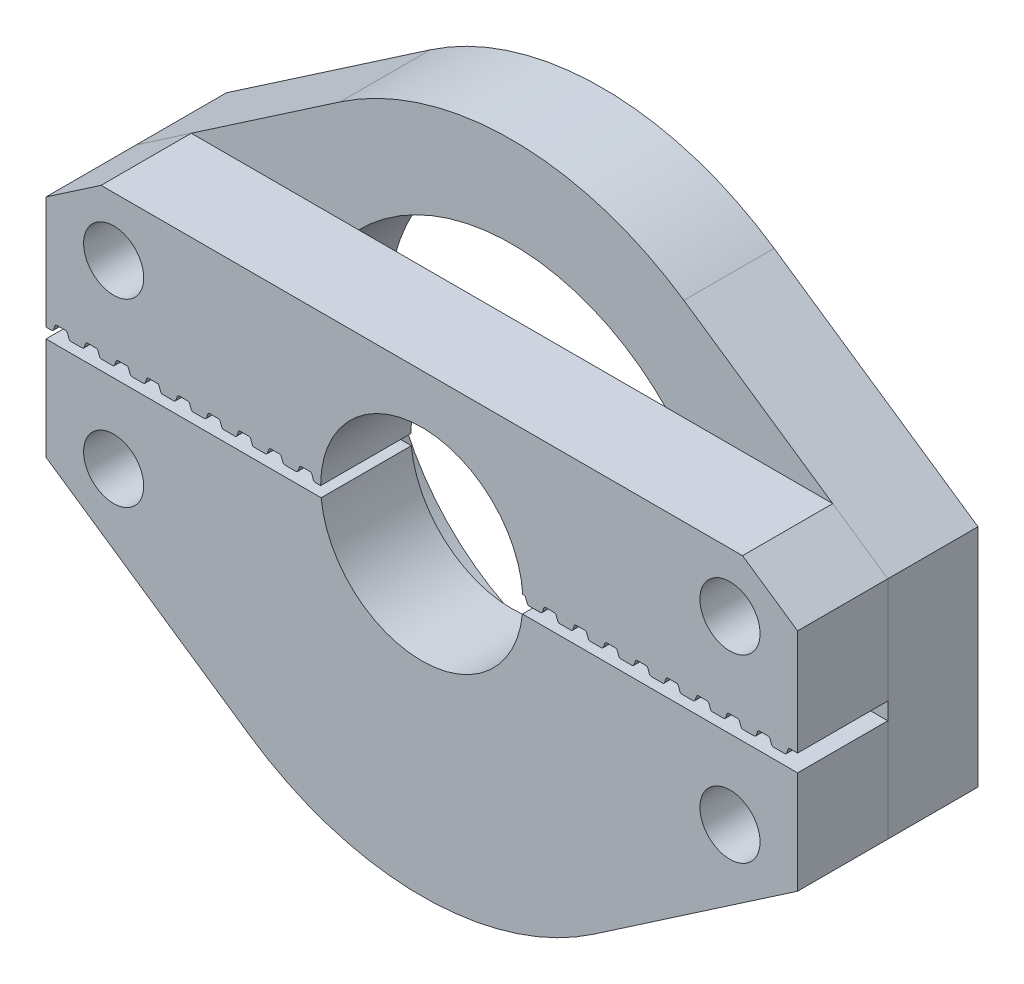
SolidWorks part; units mm, degrees
ref_plane "Front Plane" through (0, 0, 0) normal (0, 0, 1) x (1, 0, 0)
ref_plane "Top Plane" through (0, 0, 0) normal (0, 1, 0) x (1, 0, 0)
ref_plane "Right Plane" through (0, 0, 0) normal (1, 0, 0) x (0, 0, -1)
sketch "Sketch1" plane through (0, 0, 0) normal (0, 0, 1) x (1, 0, 0)
  line L0 (-45.5994, 0) -> (48.5496, 0) construction
  line L1 (-25, 7.5) -> (25, 7.5) construction
  line L2 (0, 0) -> (0, 53.2444) construction
  line L3 (-25, -7.5) -> (25, -7.5) construction
  line L4 (-25, 7.5) -> (-25, -7.5)
  line L5 (-25, -7.5) -> (-11.4362, -16.757)
  line L6 (-25, 7.5) -> (-11.4362, 16.757)
  line L7 (25, 7.5) -> (25, -7.5)
  line L8 (25, -7.5) -> (11.4362, -16.757)
  line L9 (25, 7.5) -> (11.4362, 16.757)
  circle A0 centre (0, 0) radius 14.2875
  arc A1 (-11.4362, -16.757) -> (11.4362, -16.757) centre (0, 0) ccw
  circle A2 centre (0, 0) radius 20.2875 construction
  arc A3 (11.4362, 16.757) -> (-11.4362, 16.757) centre (0, 0) ccw
  dimension "D1" = 28.575
  dimension "D3" = 50
  dimension "D4" = 15
  dimension "D2" = 6
extrude "Extrude1" add sketch "Sketch1" along normal blind 6
sketch "Sketch2" plane through (0, 0, 6) normal (0, 0, 1) x (1, 0, 0)
  line L0 (-25, 0) -> (25, 0) construction
  line L1 (-25, 7.5) -> (-25, -7.5) construction
  line L2 (25, -7.5) -> (25, 7.5) construction
  line L3 (-25, -0.68) -> (25, -0.68)
  line L4 (25, 7.5) -> (11.4362, 16.757) construction
  line L5 (-11.4362, 16.757) -> (-25, 7.5) construction
  line L6 (25, 7.5) -> (21.3369, 10)
  line L7 (-25, -0.68) -> (-25, -7.5)
  line L8 (0, 0) -> (0, 10) construction
  line L9 (-25, 0.46) -> (25, 0.46) construction
  line L10 (-25, 0) -> (-24.6225, 0)
  line L11 (-24.5003, 0.0855) -> (-24.3951, 0.3745)
  line L12 (-24.273, 0.46) -> (-23.695, 0.46)
  line L13 (-23.5729, 0.3745) -> (-23.4677, 0.0855)
  line L14 (-23.3455, 0) -> (-22.968, 0)
  line L15 (-23.984, 0.46) -> (-23.984, -0.2889) construction
  line L16 (-25, 0) -> (-25, 7.5)
  line L17 (-21.3369, 10) -> (-25, 7.5)
  line L18 (25, 7.5) -> (25, 0.46)
  line L19 (25, -0.68) -> (25, -7.5)
  line L20 (-25, -7.5) -> (-11.4362, -16.757) construction
  line L21 (11.4362, -16.757) -> (25, -7.5) construction
  line L22 (-25, -7.5) -> (-11.4362, -16.757)
  line L23 (11.4362, -16.757) -> (25, -7.5)
  line L24 (-21.3369, 10) -> (21.3369, 10)
  line L25 (0, 20.2875) -> (0, 25.9444) construction
  line L151 (-22.968, 0) -> (-22.5905, 0)
  line L152 (-22.4683, 0.0855) -> (-22.3631, 0.3745)
  line L153 (-22.241, 0.46) -> (-21.663, 0.46)
  line L154 (-21.5409, 0.3745) -> (-21.4357, 0.0855)
  line L155 (-21.3135, 0) -> (-20.936, 0)
  line L156 (-20.936, 0) -> (-20.5585, 0)
  line L157 (-20.4363, 0.0855) -> (-20.3311, 0.3745)
  line L158 (-20.209, 0.46) -> (-19.631, 0.46)
  line L159 (-19.5089, 0.3745) -> (-19.4037, 0.0855)
  line L160 (-19.2815, 0) -> (-18.904, 0)
  line L161 (-18.904, 0) -> (-18.5265, 0)
  line L162 (-18.4043, 0.0855) -> (-18.2991, 0.3745)
  line L163 (-18.177, 0.46) -> (-17.599, 0.46)
  line L164 (-17.4769, 0.3745) -> (-17.3717, 0.0855)
  line L165 (-17.2495, 0) -> (-16.872, 0)
  line L166 (-16.872, 0) -> (-16.4945, 0)
  line L167 (-16.3723, 0.0855) -> (-16.2671, 0.3745)
  line L168 (-16.145, 0.46) -> (-15.567, 0.46)
  line L169 (-15.4449, 0.3745) -> (-15.3397, 0.0855)
  line L170 (-15.2175, 0) -> (-14.84, 0)
  line L171 (-14.84, 0) -> (-14.4625, 0)
  line L172 (-14.3403, 0.0855) -> (-14.2351, 0.3745)
  line L173 (-14.113, 0.46) -> (-13.535, 0.46)
  line L174 (-13.4129, 0.3745) -> (-13.3077, 0.0855)
  line L175 (-13.1855, 0) -> (-12.808, 0)
  line L176 (-12.808, 0) -> (-12.4305, 0)
  line L177 (-12.3083, 0.0855) -> (-12.2031, 0.3745)
  line L178 (-12.081, 0.46) -> (-11.503, 0.46)
  line L179 (-11.3809, 0.3745) -> (-11.2757, 0.0855)
  line L180 (-11.1535, 0) -> (-10.776, 0)
  line L181 (-10.776, 0) -> (-10.3985, 0)
  line L182 (-10.2763, 0.0855) -> (-10.1711, 0.3745)
  line L183 (-10.049, 0.46) -> (-9.471, 0.46)
  line L184 (-9.3489, 0.3745) -> (-9.2437, 0.0855)
  line L185 (-9.1215, 0) -> (-8.744, 0)
  line L186 (-8.744, 0) -> (-8.3665, 0)
  line L187 (-8.2443, 0.0855) -> (-8.1391, 0.3745)
  line L188 (-8.017, 0.46) -> (-7.439, 0.46)
  line L189 (-7.3169, 0.3745) -> (-7.2117, 0.0855)
  line L190 (-7.0895, 0) -> (-6.712, 0)
  line L191 (-6.712, 0) -> (-6.3345, 0)
  line L192 (-6.2123, 0.0855) -> (-6.1071, 0.3745)
  line L193 (-5.985, 0.46) -> (-5.407, 0.46)
  line L194 (-5.2849, 0.3745) -> (-5.1797, 0.0855)
  line L195 (-5.0575, 0) -> (-4.68, 0)
  line L196 (-4.68, 0) -> (-4.3025, 0)
  line L197 (-4.1803, 0.0855) -> (-4.0751, 0.3745)
  line L198 (-3.953, 0.46) -> (-3.375, 0.46)
  line L199 (-3.2529, 0.3745) -> (-3.1477, 0.0855)
  line L200 (-3.0255, 0) -> (-2.648, 0)
  line L201 (-2.648, 0) -> (-2.2705, 0)
  line L202 (-2.1483, 0.0855) -> (-2.0431, 0.3745)
  line L203 (-1.921, 0.46) -> (-1.343, 0.46)
  line L204 (-1.2209, 0.3745) -> (-1.1157, 0.0855)
  line L205 (-0.9935, 0) -> (-0.616, 0)
  line L206 (-0.616, 0) -> (-0.2385, 0)
  line L207 (-0.1163, 0.0855) -> (-0.0111, 0.3745)
  line L208 (0.111, 0.46) -> (0.689, 0.46)
  line L209 (0.8111, 0.3745) -> (0.9163, 0.0855)
  line L210 (1.0385, 0) -> (1.416, 0)
  line L211 (1.416, 0) -> (1.7935, 0)
  line L212 (1.9157, 0.0855) -> (2.0209, 0.3745)
  line L213 (2.143, 0.46) -> (2.721, 0.46)
  line L214 (2.8431, 0.3745) -> (2.9483, 0.0855)
  line L215 (3.0705, 0) -> (3.448, 0)
  line L216 (3.448, 0) -> (3.8255, 0)
  line L217 (3.9477, 0.0855) -> (4.0529, 0.3745)
  line L218 (4.175, 0.46) -> (4.753, 0.46)
  line L219 (4.8751, 0.3745) -> (4.9803, 0.0855)
  line L220 (5.1025, 0) -> (5.48, 0)
  line L221 (5.48, 0) -> (5.8575, 0)
  line L222 (5.9797, 0.0855) -> (6.0849, 0.3745)
  line L223 (6.207, 0.46) -> (6.785, 0.46)
  line L224 (6.9071, 0.3745) -> (7.0123, 0.0855)
  line L225 (7.1345, 0) -> (7.512, 0)
  line L226 (7.512, 0) -> (7.8895, 0)
  line L227 (8.0117, 0.0855) -> (8.1169, 0.3745)
  line L228 (8.239, 0.46) -> (8.817, 0.46)
  line L229 (8.9391, 0.3745) -> (9.0443, 0.0855)
  line L230 (9.1665, 0) -> (9.544, 0)
  line L231 (9.544, 0) -> (9.9215, 0)
  line L232 (10.0437, 0.0855) -> (10.1489, 0.3745)
  line L233 (10.271, 0.46) -> (10.849, 0.46)
  line L234 (10.9711, 0.3745) -> (11.0763, 0.0855)
  line L235 (11.1985, 0) -> (11.576, 0)
  line L236 (11.576, 0) -> (11.9535, 0)
  line L237 (12.0757, 0.0855) -> (12.1809, 0.3745)
  line L238 (12.303, 0.46) -> (12.881, 0.46)
  line L239 (13.0031, 0.3745) -> (13.1083, 0.0855)
  line L240 (13.2305, 0) -> (13.608, 0)
  line L241 (13.608, 0) -> (13.9855, 0)
  line L242 (14.1077, 0.0855) -> (14.2129, 0.3745)
  line L243 (14.335, 0.46) -> (14.913, 0.46)
  line L244 (15.0351, 0.3745) -> (15.1403, 0.0855)
  line L245 (15.2625, 0) -> (15.64, 0)
  line L246 (15.64, 0) -> (16.0175, 0)
  line L247 (16.1397, 0.0855) -> (16.2449, 0.3745)
  line L248 (16.367, 0.46) -> (16.945, 0.46)
  line L249 (17.0671, 0.3745) -> (17.1723, 0.0855)
  line L250 (17.2945, 0) -> (17.672, 0)
  line L251 (17.672, 0) -> (18.0495, 0)
  line L252 (18.1717, 0.0855) -> (18.2769, 0.3745)
  line L253 (18.399, 0.46) -> (18.977, 0.46)
  line L254 (19.0991, 0.3745) -> (19.2043, 0.0855)
  line L255 (19.3265, 0) -> (19.704, 0)
  line L256 (19.704, 0) -> (20.0815, 0)
  line L257 (20.2037, 0.0855) -> (20.3089, 0.3745)
  line L258 (20.431, 0.46) -> (21.009, 0.46)
  line L259 (21.1311, 0.3745) -> (21.2363, 0.0855)
  line L260 (21.3585, 0) -> (21.736, 0)
  line L261 (21.736, 0) -> (22.1135, 0)
  line L262 (22.2357, 0.0855) -> (22.3409, 0.3745)
  line L263 (22.463, 0.46) -> (23.041, 0.46)
  line L264 (23.1631, 0.3745) -> (23.2683, 0.0855)
  line L265 (23.3905, 0) -> (23.768, 0)
  line L266 (23.768, 0) -> (24.1455, 0)
  line L267 (24.2677, 0.0855) -> (24.3729, 0.3745)
  line L268 (24.495, 0.46) -> (25, 0.46)
  line L296 (35.3551, 0.3745) -> (35.4603, 0.0855) [skipped]
  line L297 (35.5825, 0) -> (35.96, 0) [skipped]
  line L298 (25.1951, 0.3745) -> (25.3003, 0.0855) [skipped]
  line L299 (25.4225, 0) -> (25.8, 0) [skipped]
  line L300 (25.8, 0) -> (26.1775, 0) [skipped]
  line L301 (26.2997, 0.0855) -> (26.4049, 0.3745) [skipped]
  line L302 (26.527, 0.46) -> (27.105, 0.46) [skipped]
  line L303 (27.2271, 0.3745) -> (27.3323, 0.0855) [skipped]
  line L304 (27.4545, 0) -> (27.832, 0) [skipped]
  line L305 (27.832, 0) -> (28.2095, 0) [skipped]
  line L306 (28.3317, 0.0855) -> (28.4369, 0.3745) [skipped]
  line L307 (28.559, 0.46) -> (29.137, 0.46) [skipped]
  line L308 (29.2591, 0.3745) -> (29.3643, 0.0855) [skipped]
  line L309 (29.4865, 0) -> (29.864, 0) [skipped]
  line L310 (29.864, 0) -> (30.2415, 0) [skipped]
  line L311 (30.3637, 0.0855) -> (30.4689, 0.3745) [skipped]
  line L312 (30.591, 0.46) -> (31.169, 0.46) [skipped]
  line L313 (31.2911, 0.3745) -> (31.3963, 0.0855) [skipped]
  line L314 (31.5185, 0) -> (31.896, 0) [skipped]
  line L315 (31.896, 0) -> (32.2735, 0) [skipped]
  line L316 (32.3957, 0.0855) -> (32.5009, 0.3745) [skipped]
  line L317 (32.623, 0.46) -> (33.201, 0.46) [skipped]
  line L318 (33.3231, 0.3745) -> (33.4283, 0.0855) [skipped]
  line L319 (33.5505, 0) -> (33.928, 0) [skipped]
  line L320 (33.928, 0) -> (34.3055, 0) [skipped]
  line L321 (34.4277, 0.0855) -> (34.5329, 0.3745) [skipped]
  line L322 (34.655, 0.46) -> (26.527, 0.46) [skipped]
  arc A0 (-24.5003, 0.0855) -> (-24.6225, 0) centre (-24.6225, 0.13) cw
  arc A1 (-24.273, 0.46) -> (-24.3951, 0.3745) centre (-24.273, 0.33) ccw
  arc A2 (-23.5729, 0.3745) -> (-23.695, 0.46) centre (-23.695, 0.33) ccw
  arc A3 (-23.3455, 0) -> (-23.4677, 0.0855) centre (-23.3455, 0.13) cw
  arc A6 (-11.4362, -16.757) -> (11.4362, -16.757) centre (0, 0) ccw construction
  arc A7 (-11.4362, -16.757) -> (11.4362, -16.757) centre (0, 0) ccw
  arc A112 (-22.4683, 0.0855) -> (-22.5905, 0) centre (-22.5905, 0.13) cw
  arc A113 (-22.241, 0.46) -> (-22.3631, 0.3745) centre (-22.241, 0.33) ccw
  arc A114 (-21.5409, 0.3745) -> (-21.663, 0.46) centre (-21.663, 0.33) ccw
  arc A115 (-21.3135, 0) -> (-21.4357, 0.0855) centre (-21.3135, 0.13) cw
  arc A116 (-20.4363, 0.0855) -> (-20.5585, 0) centre (-20.5585, 0.13) cw
  arc A117 (-20.209, 0.46) -> (-20.3311, 0.3745) centre (-20.209, 0.33) ccw
  arc A118 (-19.5089, 0.3745) -> (-19.631, 0.46) centre (-19.631, 0.33) ccw
  arc A119 (-19.2815, 0) -> (-19.4037, 0.0855) centre (-19.2815, 0.13) cw
  arc A120 (-18.4043, 0.0855) -> (-18.5265, 0) centre (-18.5265, 0.13) cw
  arc A121 (-18.177, 0.46) -> (-18.2991, 0.3745) centre (-18.177, 0.33) ccw
  arc A122 (-17.4769, 0.3745) -> (-17.599, 0.46) centre (-17.599, 0.33) ccw
  arc A123 (-17.2495, 0) -> (-17.3717, 0.0855) centre (-17.2495, 0.13) cw
  arc A124 (-16.3723, 0.0855) -> (-16.4945, 0) centre (-16.4945, 0.13) cw
  arc A125 (-16.145, 0.46) -> (-16.2671, 0.3745) centre (-16.145, 0.33) ccw
  arc A126 (-15.4449, 0.3745) -> (-15.567, 0.46) centre (-15.567, 0.33) ccw
  arc A127 (-15.2175, 0) -> (-15.3397, 0.0855) centre (-15.2175, 0.13) cw
  arc A128 (-14.3403, 0.0855) -> (-14.4625, 0) centre (-14.4625, 0.13) cw
  arc A129 (-14.113, 0.46) -> (-14.2351, 0.3745) centre (-14.113, 0.33) ccw
  arc A130 (-13.4129, 0.3745) -> (-13.535, 0.46) centre (-13.535, 0.33) ccw
  arc A131 (-13.1855, 0) -> (-13.3077, 0.0855) centre (-13.1855, 0.13) cw
  arc A132 (-12.3083, 0.0855) -> (-12.4305, 0) centre (-12.4305, 0.13) cw
  arc A133 (-12.081, 0.46) -> (-12.2031, 0.3745) centre (-12.081, 0.33) ccw
  arc A134 (-11.3809, 0.3745) -> (-11.503, 0.46) centre (-11.503, 0.33) ccw
  arc A135 (-11.1535, 0) -> (-11.2757, 0.0855) centre (-11.1535, 0.13) cw
  arc A136 (-10.2763, 0.0855) -> (-10.3985, 0) centre (-10.3985, 0.13) cw
  arc A137 (-10.049, 0.46) -> (-10.1711, 0.3745) centre (-10.049, 0.33) ccw
  arc A138 (-9.3489, 0.3745) -> (-9.471, 0.46) centre (-9.471, 0.33) ccw
  arc A139 (-9.1215, 0) -> (-9.2437, 0.0855) centre (-9.1215, 0.13) cw
  arc A140 (-8.2443, 0.0855) -> (-8.3665, 0) centre (-8.3665, 0.13) cw
  arc A141 (-8.017, 0.46) -> (-8.1391, 0.3745) centre (-8.017, 0.33) ccw
  arc A142 (-7.3169, 0.3745) -> (-7.439, 0.46) centre (-7.439, 0.33) ccw
  arc A143 (-7.0895, 0) -> (-7.2117, 0.0855) centre (-7.0895, 0.13) cw
  arc A144 (-6.2123, 0.0855) -> (-6.3345, 0) centre (-6.3345, 0.13) cw
  arc A145 (-5.985, 0.46) -> (-6.1071, 0.3745) centre (-5.985, 0.33) ccw
  arc A146 (-5.2849, 0.3745) -> (-5.407, 0.46) centre (-5.407, 0.33) ccw
  arc A147 (-5.0575, 0) -> (-5.1797, 0.0855) centre (-5.0575, 0.13) cw
  arc A148 (-4.1803, 0.0855) -> (-4.3025, 0) centre (-4.3025, 0.13) cw
  arc A149 (-3.953, 0.46) -> (-4.0751, 0.3745) centre (-3.953, 0.33) ccw
  arc A150 (-3.2529, 0.3745) -> (-3.375, 0.46) centre (-3.375, 0.33) ccw
  arc A151 (-3.0255, 0) -> (-3.1477, 0.0855) centre (-3.0255, 0.13) cw
  arc A152 (-2.1483, 0.0855) -> (-2.2705, 0) centre (-2.2705, 0.13) cw
  arc A153 (-1.921, 0.46) -> (-2.0431, 0.3745) centre (-1.921, 0.33) ccw
  arc A154 (-1.2209, 0.3745) -> (-1.343, 0.46) centre (-1.343, 0.33) ccw
  arc A155 (-0.9935, 0) -> (-1.1157, 0.0855) centre (-0.9935, 0.13) cw
  arc A156 (-0.1163, 0.0855) -> (-0.2385, 0) centre (-0.2385, 0.13) cw
  arc A157 (0.111, 0.46) -> (-0.0111, 0.3745) centre (0.111, 0.33) ccw
  arc A158 (0.8111, 0.3745) -> (0.689, 0.46) centre (0.689, 0.33) ccw
  arc A159 (1.0385, 0) -> (0.9163, 0.0855) centre (1.0385, 0.13) cw
  arc A160 (1.9157, 0.0855) -> (1.7935, 0) centre (1.7935, 0.13) cw
  arc A161 (2.143, 0.46) -> (2.0209, 0.3745) centre (2.143, 0.33) ccw
  arc A162 (2.8431, 0.3745) -> (2.721, 0.46) centre (2.721, 0.33) ccw
  arc A163 (3.0705, 0) -> (2.9483, 0.0855) centre (3.0705, 0.13) cw
  arc A164 (3.9477, 0.0855) -> (3.8255, 0) centre (3.8255, 0.13) cw
  arc A165 (4.175, 0.46) -> (4.0529, 0.3745) centre (4.175, 0.33) ccw
  arc A166 (4.8751, 0.3745) -> (4.753, 0.46) centre (4.753, 0.33) ccw
  arc A167 (5.1025, 0) -> (4.9803, 0.0855) centre (5.1025, 0.13) cw
  arc A168 (5.9797, 0.0855) -> (5.8575, 0) centre (5.8575, 0.13) cw
  arc A169 (6.207, 0.46) -> (6.0849, 0.3745) centre (6.207, 0.33) ccw
  arc A170 (6.9071, 0.3745) -> (6.785, 0.46) centre (6.785, 0.33) ccw
  arc A171 (7.1345, 0) -> (7.0123, 0.0855) centre (7.1345, 0.13) cw
  arc A172 (8.0117, 0.0855) -> (7.8895, 0) centre (7.8895, 0.13) cw
  arc A173 (8.239, 0.46) -> (8.1169, 0.3745) centre (8.239, 0.33) ccw
  arc A174 (8.9391, 0.3745) -> (8.817, 0.46) centre (8.817, 0.33) ccw
  arc A175 (9.1665, 0) -> (9.0443, 0.0855) centre (9.1665, 0.13) cw
  arc A176 (10.0437, 0.0855) -> (9.9215, 0) centre (9.9215, 0.13) cw
  arc A177 (10.271, 0.46) -> (10.1489, 0.3745) centre (10.271, 0.33) ccw
  arc A178 (10.9711, 0.3745) -> (10.849, 0.46) centre (10.849, 0.33) ccw
  arc A179 (11.1985, 0) -> (11.0763, 0.0855) centre (11.1985, 0.13) cw
  arc A180 (12.0757, 0.0855) -> (11.9535, 0) centre (11.9535, 0.13) cw
  arc A181 (12.303, 0.46) -> (12.1809, 0.3745) centre (12.303, 0.33) ccw
  arc A182 (13.0031, 0.3745) -> (12.881, 0.46) centre (12.881, 0.33) ccw
  arc A183 (13.2305, 0) -> (13.1083, 0.0855) centre (13.2305, 0.13) cw
  arc A184 (14.1077, 0.0855) -> (13.9855, 0) centre (13.9855, 0.13) cw
  arc A185 (14.335, 0.46) -> (14.2129, 0.3745) centre (14.335, 0.33) ccw
  arc A186 (15.0351, 0.3745) -> (14.913, 0.46) centre (14.913, 0.33) ccw
  arc A187 (15.2625, 0) -> (15.1403, 0.0855) centre (15.2625, 0.13) cw
  arc A188 (16.1397, 0.0855) -> (16.0175, 0) centre (16.0175, 0.13) cw
  arc A189 (16.367, 0.46) -> (16.2449, 0.3745) centre (16.367, 0.33) ccw
  arc A190 (17.0671, 0.3745) -> (16.945, 0.46) centre (16.945, 0.33) ccw
  arc A191 (17.2945, 0) -> (17.1723, 0.0855) centre (17.2945, 0.13) cw
  arc A192 (18.1717, 0.0855) -> (18.0495, 0) centre (18.0495, 0.13) cw
  arc A193 (18.399, 0.46) -> (18.2769, 0.3745) centre (18.399, 0.33) ccw
  arc A194 (19.0991, 0.3745) -> (18.977, 0.46) centre (18.977, 0.33) ccw
  arc A195 (19.3265, 0) -> (19.2043, 0.0855) centre (19.3265, 0.13) cw
  arc A196 (20.2037, 0.0855) -> (20.0815, 0) centre (20.0815, 0.13) cw
  arc A197 (20.431, 0.46) -> (20.3089, 0.3745) centre (20.431, 0.33) ccw
  arc A198 (21.1311, 0.3745) -> (21.009, 0.46) centre (21.009, 0.33) ccw
  arc A199 (21.3585, 0) -> (21.2363, 0.0855) centre (21.3585, 0.13) cw
  arc A200 (22.2357, 0.0855) -> (22.1135, 0) centre (22.1135, 0.13) cw
  arc A201 (22.463, 0.46) -> (22.3409, 0.3745) centre (22.463, 0.33) ccw
  arc A202 (23.1631, 0.3745) -> (23.041, 0.46) centre (23.041, 0.33) ccw
  arc A203 (23.3905, 0) -> (23.2683, 0.0855) centre (23.3905, 0.13) cw
  arc A204 (24.2677, 0.0855) -> (24.1455, 0) centre (24.1455, 0.13) cw
  arc A205 (24.495, 0.46) -> (24.3729, 0.3745) centre (24.495, 0.33) ccw
  arc A228 (35.3551, 0.3745) -> (35.233, 0.46) centre (35.233, 0.33) ccw [skipped]
  arc A229 (35.5825, 0) -> (35.4603, 0.0855) centre (35.5825, 0.13) cw [skipped]
  arc A230 (25.4225, 0) -> (25.3003, 0.0855) centre (25.4225, 0.13) cw [skipped]
  arc A231 (25.1951, 0.3745) -> (25.073, 0.46) centre (25.073, 0.33) ccw [skipped]
  arc A232 (26.2997, 0.0855) -> (26.1775, 0) centre (26.1775, 0.13) cw [skipped]
  arc A233 (26.527, 0.46) -> (26.4049, 0.3745) centre (26.527, 0.33) ccw [skipped]
  arc A234 (27.2271, 0.3745) -> (27.105, 0.46) centre (27.105, 0.33) ccw [skipped]
  arc A235 (27.4545, 0) -> (27.3323, 0.0855) centre (27.4545, 0.13) cw [skipped]
  arc A236 (28.3317, 0.0855) -> (28.2095, 0) centre (28.2095, 0.13) cw [skipped]
  arc A237 (28.559, 0.46) -> (28.4369, 0.3745) centre (28.559, 0.33) ccw [skipped]
  arc A238 (29.2591, 0.3745) -> (29.137, 0.46) centre (29.137, 0.33) ccw [skipped]
  arc A239 (29.4865, 0) -> (29.3643, 0.0855) centre (29.4865, 0.13) cw [skipped]
  arc A240 (30.3637, 0.0855) -> (30.2415, 0) centre (30.2415, 0.13) cw [skipped]
  arc A241 (30.591, 0.46) -> (30.4689, 0.3745) centre (30.591, 0.33) ccw [skipped]
  arc A242 (31.2911, 0.3745) -> (31.169, 0.46) centre (31.169, 0.33) ccw [skipped]
  arc A243 (31.5185, 0) -> (31.3963, 0.0855) centre (31.5185, 0.13) cw [skipped]
  arc A244 (32.3957, 0.0855) -> (32.2735, 0) centre (32.2735, 0.13) cw [skipped]
  arc A245 (32.623, 0.46) -> (32.5009, 0.3745) centre (32.623, 0.33) ccw [skipped]
  arc A246 (33.3231, 0.3745) -> (33.201, 0.46) centre (33.201, 0.33) ccw [skipped]
  arc A247 (33.5505, 0) -> (33.4283, 0.0855) centre (33.5505, 0.13) cw [skipped]
  arc A248 (34.4277, 0.0855) -> (34.3055, 0) centre (34.3055, 0.13) cw [skipped]
  arc A249 (34.655, 0.46) -> (34.5329, 0.3745) centre (34.655, 0.33) ccw [skipped]
  point P27 (-24.5314, 0)
  point P30 (-24.364, 0.46)
  point P33 (-23.604, 0.46)
  point P36 (-23.4366, 0)
  dimension "D6" = 0.13
  dimension "D1" = 0.68
  dimension "D2" = 0.46
  dimension "D3" = 40
  dimension "D4" = 0.76
  dimension "D5" = 0.636
  dimension "D7" = 10
extrude "Extrude2" add sketch "Sketch2" along normal blind 6 separate body
sketch "Sketch3" plane through (0, 0, 12) normal (0, 0, 1) x (1, 0, 0)
  line L0 (-20.5, 10.5711) -> (-20.5, -10.5711) construction
  line L1 (-21.3369, 10) -> (-25, 7.5) construction
  line L2 (-25, -7.5) -> (-11.4362, -16.757) construction
  line L3 (0, 10) -> (0, -20.2875) construction
  line L4 (-9.2437, 0.0855) -> (-34.7364, 0.0855) construction
  line L5 (21.3369, 10) -> (-21.3369, 10) construction
  arc A1 (-11.4362, -16.757) -> (11.4362, -16.757) centre (0, 0) ccw construction
  circle A2 centre (-20.5, 6.0855) radius 2
  circle A3 centre (-20.5, -5.9145) radius 2
  circle A4 centre (20.5, -5.9145) radius 2
  circle A5 centre (20.5, 6.0855) radius 2
  dimension "D3" = 4
  dimension "D1" = 41
  dimension "D2" = 12
extrude "Extrude3" cut sketch "Sketch3" against normal through all
sketch "Sketch4" plane through (0, 0, 6) normal (0, 0, -1) x (-1, 0, 0)
  circle A0 centre (0, 0) radius 14.2875 construction
  circle A1 centre (0, 0) radius 14.2875 construction
  circle A2 centre (0, 0) radius 6.731
  dimension "D1" = 13.462
extrude "Extrude4" cut sketch "Sketch4" against normal blind 10
